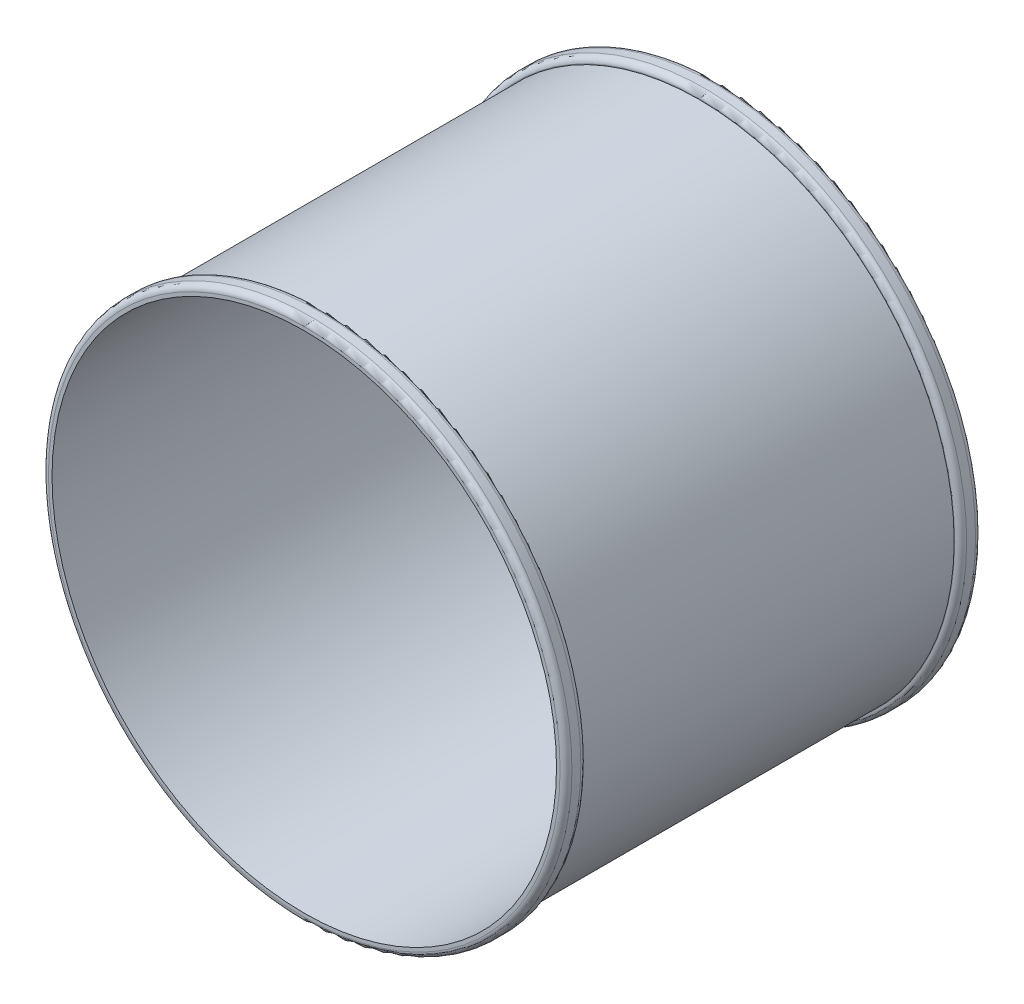
SolidWorks part; units mm, degrees
ref_plane "Front Plane" through (0, 0, 0) normal (0, 0, 1) x (1, 0, 0)
ref_plane "Top Plane" through (0, 0, 0) normal (0, 1, 0) x (1, 0, 0)
ref_plane "Right Plane" through (0, 0, 0) normal (1, 0, 0) x (0, 0, -1)
sketch "Sketch1" plane through (0, 0, 0) normal (0, 0, 1) x (1, 0, 0)
  circle A0 centre (0, 0) radius 42.5
  dimension "D1" = 85
extrude "Extrude-Thin1" add sketch "Sketch1" along normal mid plane 70 thin
sketch "Sketch2" plane through (0, 0, 35) normal (0, 0, 1) x (1, 0, 0)
  circle A0 centre (0, 0) radius 42.5 construction
  circle A1 centre (0, 0) radius 42.5
extrude "Extrude-Thin2" add sketch "Sketch2" against normal blind 3.5 thin
fillet "Fillet1" radius 1 2 edges at (44.1, 0, 31.5) (44.1, 0, 35)
mirror "Mirror1" about plane through (0, 0, 0) normal (0, 0, 1) of "Fillet1", "Extrude-Thin2"
